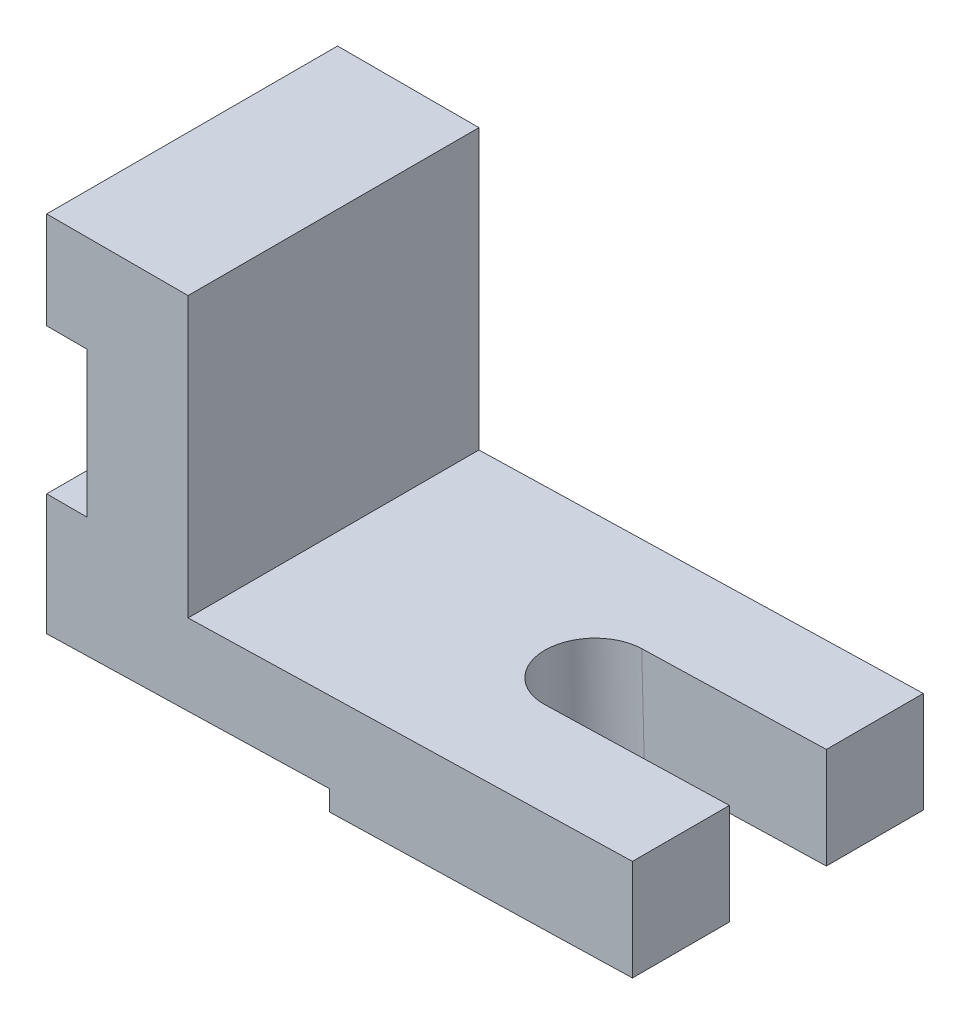
SolidWorks part; units mm, degrees
ref_plane "Front Plane" through (0, 0, 0) normal (0, 0, 1) x (1, 0, 0)
ref_plane "Top Plane" through (0, 0, 0) normal (0, 1, 0) x (1, 0, 0)
ref_plane "Right Plane" through (0, 0, 0) normal (1, 0, 0) x (0, 0, -1)
sketch "Sketch1" plane through (0, 0, 0) normal (0, 0, 1) x (1, 0, 0)
  line L0 (0, 0) -> (70, 1.7878)
  line L1 (70, 1.7878) -> (70, -3.2122)
  line L2 (70, -3.2122) -> (145, -1.2967)
  line L3 (145, -1.2967) -> (145, 23.7033)
  line L4 (145, 23.7033) -> (35, 20.8939)
  line L5 (35, 20.8939) -> (35, 90)
  line L6 (35, 90) -> (0, 90)
  line L7 (0, 90) -> (0, 0)
  dimension "D1" = 70
  dimension "D2" = 145
  dimension "D3" = 90
  dimension "D4" = 35
  dimension "D5" = 5
  dimension "D6" = 25
extrude "Boss-Extrude1" add sketch "Sketch1" against normal blind 72
sketch "Sketch2" plane through (0, 0, 0) normal (0, 0, 1) x (1, 0, 0)
  line L0 (0, 90) -> (0, 0) construction
  line L1 (0, 66) -> (10, 66)
  line L2 (0, 66) -> (0, 30)
  line L3 (0, 30) -> (10, 30)
  line L4 (10, 66) -> (10, 30)
  line L5 (35, 90) -> (0, 90) construction
  dimension "D1" = 24
  dimension "D2" = 36
  dimension "D3" = 10
extrude "Cut-Extrude1" cut sketch "Sketch2" against normal blind 72
sketch "Sketch3" plane through (0, 0, 0) normal (1, 0, 0) x (0, 0, -1)
  line L1 (59.7233, 66) -> (11.8855, 66)
  line L2 (72, 66) -> (0, 66) construction
  line L3 (59.8848, 30) -> (11.7241, 30)
  line L4 (72, 30) -> (0, 30) construction
  circle A1 centre (35.8044, 47.8924) radius 12
  arc A2 (59.7233, 66) -> (11.8855, 66) centre (35.8044, 47.8924) ccw
  arc A3 (11.7241, 30) -> (59.8848, 30) centre (35.8044, 47.8924) ccw
  dimension "D1" = 60
extrude "Cut-Extrude3" cut sketch "Sketch3" along normal blind 12
sketch "Sketch4" plane through (-0.5105, 19.987, 0) normal (-0.0255, 0.9997, 0) x (0.9997, 0.0255, 0)
  line L0 (99.9413, 35.9204) -> (145.5579, 36) construction
  line L1 (145.5579, 72) -> (145.5579, 0) construction
  line L2 (99.9204, 47.9204) -> (145.537, 48)
  line L3 (99.9623, 23.9204) -> (145.5789, 24)
  arc A0 (99.9204, 47.9204) -> (99.9623, 23.9204) centre (99.9413, 35.9204) ccw
  arc A1 (145.5789, 24) -> (145.537, 48) centre (145.5579, 36) ccw
  point P4 (122.7496, 35.9602)
  point P9 (99.9413, 35.9204)
  dimension "D1" = 12
  dimension "D2" = 24
extrude "Cut-Extrude4" cut sketch "Sketch4" against normal blind 32
sketch "Sketch5" plane through (0, 0, 0) normal (0.0255, -0.9997, 0) x (0.9997, 0.0255, 0)
  line L0 (70.0228, -72) -> (70.0228, 0) construction
  line L1 (0, -72) -> (70.0228, -72)
  line L2 (0, -72) -> (0, -60)
  line L3 (0, -60) -> (70.0228, -60)
  line L4 (70.0228, -72) -> (70.0228, -60)
  dimension "D1" = 12
extrude "Boss-Extrude2" add sketch "Sketch5" along normal blind 5
